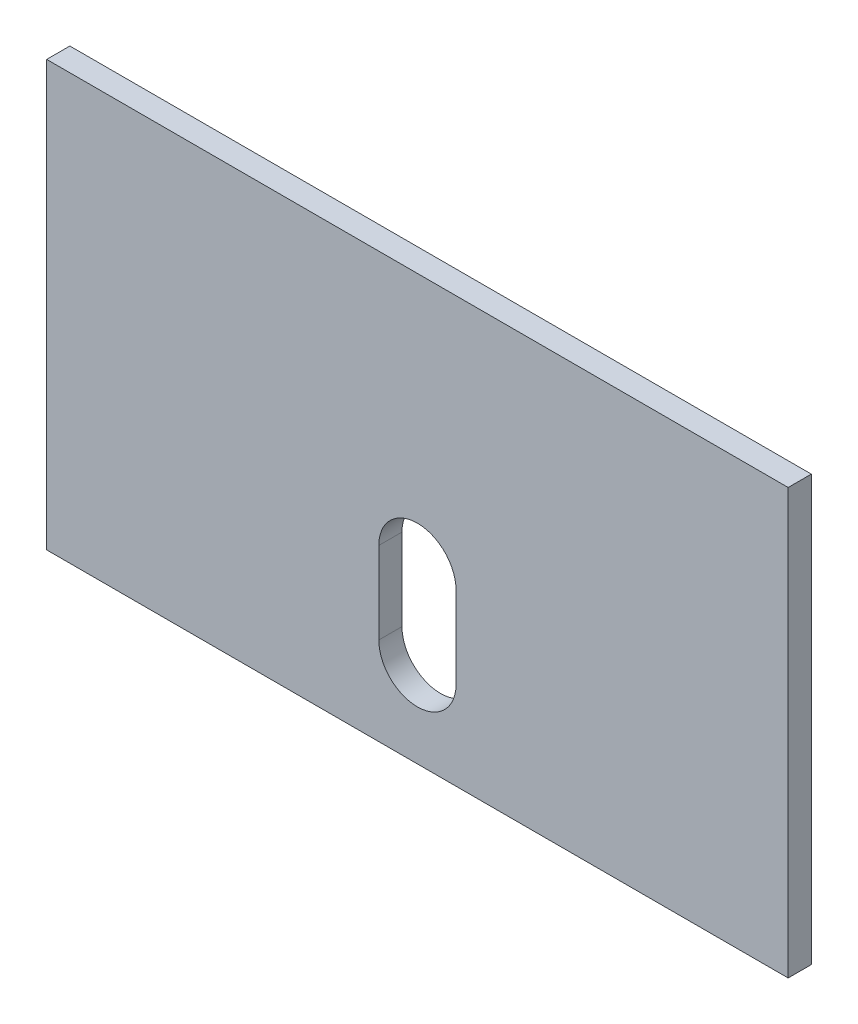
SolidWorks part; units mm, degrees
material "3.0517 (EN-AW 3003)"
ref_plane "Front Plane" through (0, 0, 0) normal (0, 0, 1) x (1, 0, 0)
ref_plane "Top Plane" through (0, 0, 0) normal (0, 1, 0) x (1, 0, 0)
ref_plane "Right Plane" through (0, 0, 0) normal (1, 0, 0) x (0, 0, -1)
sketch "Sketch1" plane through (0, 0, 0) normal (0, 0, 1) x (1, 0, 0)
  line L0 (0, -16.1) -> (0, -5.5) construction
  line L1 (48, -27.5) -> (-48, -27.5)
  line L2 (48, -27.5) -> (48, 27.5)
  line L3 (48, 27.5) -> (-48, 27.5)
  line L4 (-48, -27.5) -> (-48, 27.5)
  line L5 (48, -27.5) -> (-48, 27.5) construction
  line L6 (48, 27.5) -> (-48, -27.5) construction
  line L7 (-5, -16.1) -> (-5, -5.5)
  line L8 (5, -16.1) -> (5, -5.5)
  arc A0 (-5, -16.1) -> (5, -16.1) centre (0, -16.1) ccw
  arc A1 (5, -5.5) -> (-5, -5.5) centre (0, -5.5) ccw
  point P0 (0, 0)
  point P8 (0, -10.8)
  dimension "D4" = 5
  dimension "D1" = 55
  dimension "D2" = 96
  dimension "D3" = 10.6
  dimension "D5" = 11.4
extrude "Boss-Extrude1" add sketch "Sketch1" along normal mid plane 3
